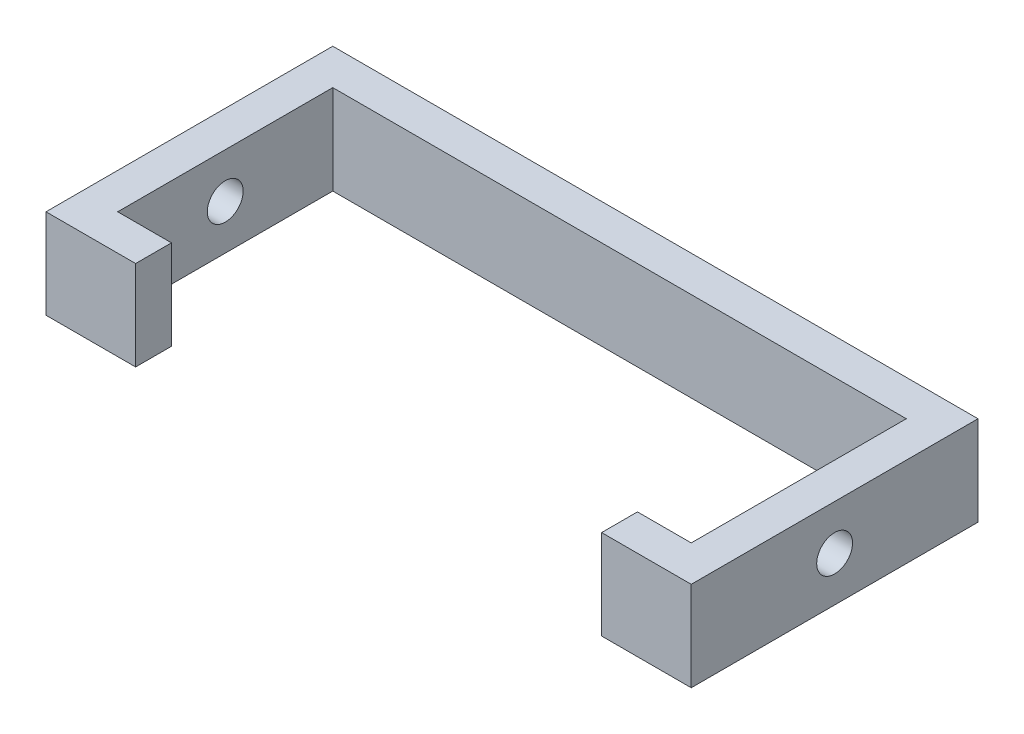
SolidWorks part; units mm, degrees
ref_plane "Front Plane" through (0, 0, 0) normal (0, 0, 1) x (1, 0, 0)
ref_plane "Top Plane" through (0, 0, 0) normal (0, 1, 0) x (1, 0, 0)
ref_plane "Right Plane" through (0, 0, 0) normal (1, 0, 0) x (0, 0, -1)
sketch "Sketch1" plane through (0, 0, 0) normal (0, 1, 0) x (1, 0, 0)
  line L0 (13, -6) -> (13, -8)
  line L1 (-16, 6) -> (16, 6)
  line L2 (-16, 6) -> (-16, -6)
  line L3 (-16, -6) -> (16, -6) construction
  line L4 (16, 6) -> (16, -6)
  line L5 (-16, 6) -> (16, -6) construction
  line L6 (-16, -6) -> (16, 6) construction
  line L7 (-18, 8) -> (18, 8)
  line L8 (-18, 8) -> (-18, -8)
  line L9 (-18, -8) -> (18, -8) construction
  line L10 (18, 8) -> (18, -8)
  line L11 (-18, 8) -> (18, -8) construction
  line L12 (-18, -8) -> (18, 8) construction
  line L13 (16, -6) -> (13, -6)
  line L14 (18, -8) -> (13, -8)
  line L15 (-13, -6) -> (-13, -8)
  line L16 (-16, -6) -> (-13, -6)
  line L17 (-13, -8) -> (-18, -8)
  point P0 (0, 0)
  point P6 (0, 0)
  dimension "D1" = 32
  dimension "D2" = 12
  dimension "D3" = 36
  dimension "D4" = 16
  dimension "D5" = 5
  dimension "D6" = 5
extrude "Boss-Extrude1" add sketch "Sketch1" along normal mid plane 5
sketch "Sketch2" plane through (18, 0, 0) normal (1, 0, 0) x (0, 0, -1)
  circle A0 centre (0, 0) radius 1
  dimension "D1" = 2
extrude "Cut-Extrude1" cut sketch "Sketch2" against normal through all both and the other way through all
